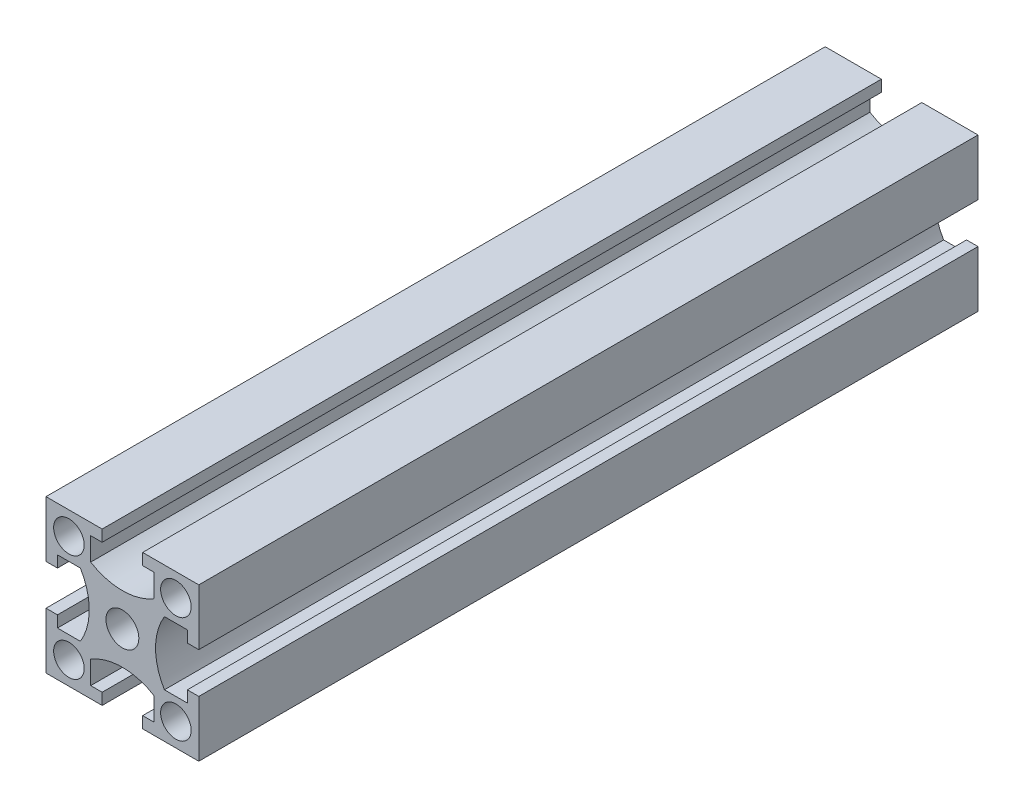
SolidWorks part; units mm, degrees
material "6061-T6 (SS)"
ref_plane "정면" through (0, 0, 0) normal (0, 0, 1) x (1, 0, 0)
ref_plane "윗면" through (0, 0, 0) normal (0, 1, 0) x (1, 0, 0)
ref_plane "우측면" through (0, 0, 0) normal (1, 0, 0) x (0, 0, -1)
sketch "스케치1" plane through (0, 0, 0) normal (0, 0, 1) x (1, 0, 0)
  line L1 (-10, 10) -> (10, 10)
  line L2 (-10, 10) -> (-10, -10)
  line L3 (-10, -10) -> (10, -10)
  line L4 (10, 10) -> (10, -10)
  line L5 (-10, 10) -> (10, -10) construction
  line L6 (-10, -10) -> (10, 10) construction
  point P0 (0, 0)
  dimension "D1" = 20
  dimension "D2" = 20
extrude "보스-돌출1" add sketch "스케치1" along normal blind 102
sketch "스케치2" plane through (0, 0, 102) normal (0, 0, 1) x (1, 0, 0)
  line L0 (-2.65, 10) -> (-2.65, 8.5)
  line L1 (10, 10) -> (-10, 10) construction
  line L2 (-2.65, 8.5) -> (-4.15, 8.5)
  line L3 (-4.15, 8.5) -> (-4.15, 5.5)
  line L4 (-2.65, 10) -> (2.65, 10)
  line L5 (2.65, 10) -> (2.65, 8.5)
  line L6 (2.65, 8.5) -> (4.15, 8.5)
  line L7 (4.15, 8.5) -> (4.15, 5.5)
  line L8 (10, 2.65) -> (8.5, 2.65)
  line L9 (8.5, 2.65) -> (8.5, 4.15)
  line L10 (8.5, 4.15) -> (5.5, 4.15)
  line L11 (10, 2.65) -> (10, -2.65)
  line L12 (10, -2.65) -> (8.5, -2.65)
  line L13 (8.5, -2.65) -> (8.5, -4.15)
  line L14 (8.5, -4.15) -> (5.5, -4.15)
  line L15 (2.65, -10) -> (2.65, -8.5)
  line L16 (2.65, -8.5) -> (4.15, -8.5)
  line L17 (4.15, -8.5) -> (4.15, -5.5)
  line L18 (2.65, -10) -> (-2.65, -10)
  line L19 (-2.65, -10) -> (-2.65, -8.5)
  line L20 (-2.65, -8.5) -> (-4.15, -8.5)
  line L21 (-4.15, -8.5) -> (-4.15, -5.5)
  line L22 (-10, -2.65) -> (-8.5, -2.65)
  line L23 (-8.5, -2.65) -> (-8.5, -4.15)
  line L24 (-8.5, -4.15) -> (-5.5, -4.15)
  line L25 (-10, -2.65) -> (-10, 2.65)
  line L26 (-10, 2.65) -> (-8.5, 2.65)
  line L27 (-8.5, 2.65) -> (-8.5, 4.15)
  line L28 (-8.5, 4.15) -> (-5.5, 4.15)
  arc A1 (-4.15, 5.5) -> (4.15, 5.5) centre (0, 12.3394) ccw
  arc A2 (5.5, 4.15) -> (5.5, -4.15) centre (12.3394, 0) ccw
  arc A3 (4.15, -5.5) -> (-4.15, -5.5) centre (0, -12.3394) ccw
  arc A4 (-5.5, -4.15) -> (-5.5, 4.15) centre (-12.3394, 0) ccw
  circle A5 centre (0, 0) radius 2.15
  circle A6 centre (-7, 7) radius 2
  circle A7 centre (7, 7) radius 2
  circle A8 centre (7, -7) radius 2
  circle A9 centre (-7, -7) radius 2
  point P4 (-2.65, 9.25)
  point P43 (0, 0)
  dimension "D2" = 1.5
  dimension "D8" = 4.3
  dimension "D9" = 4
  dimension "D10" = 4
  dimension "D11" = 4
  dimension "D12" = 4
  dimension "D21" = 8
  dimension "D1" = 5.3
  dimension "D3" = 8.3
  dimension "D4" = 4.15
  dimension "D5" = 2.65
  dimension "D6" = 4
  dimension "D7" = 3
  dimension "D13" = 14
  dimension "D14" = 7
  dimension "D15" = 7
  dimension "D16" = 7
  dimension "D17" = 14
  dimension "D18" = 7
  dimension "D19" = 7
  dimension "D20" = 7
extrude "컷-돌출1" cut sketch "스케치2" against normal blind 300
